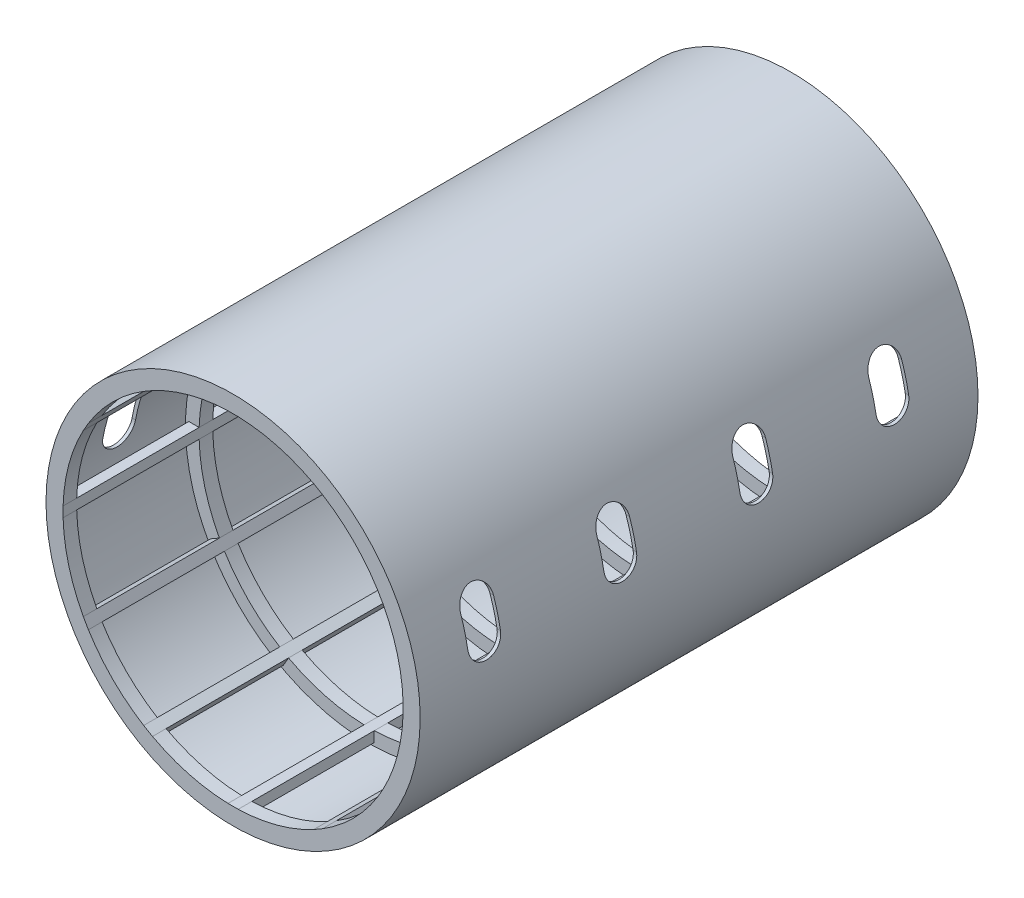
SolidWorks part; units mm, degrees
ref_plane "Front Plane" through (0, 0, 0) normal (0, 0, 1) x (1, 0, 0)
ref_plane "Top Plane" through (0, 0, 0) normal (0, 1, 0) x (1, 0, 0)
ref_plane "Right Plane" through (0, 0, 0) normal (1, 0, 0) x (0, 0, -1)
sketch "Sketch2" plane through (0, 0, 0) normal (0, 0, 1) x (1, 0, 0)
  circle A0 centre (0, 0) radius 25
  circle A1 centre (0, 0) radius 27
  dimension "D1" = 50
  dimension "D2" = 54
extrude "Boss-Extrude1" add sketch "Sketch2" along normal blind 2
sketch "Sketch3" plane through (0, 0, 2) normal (0, 0, 1) x (1, 0, 0)
  line L0 (12.6005, 23.3247) -> (11.1005, 20.7266)
  line L1 (-0.75, 26.5) -> (0.75, 26.5)
  line L2 (-0.75, 26.5) -> (-0.75, 23.5)
  line L3 (-0.75, 23.5) -> (0.75, 23.5)
  line L4 (0.75, 26.5) -> (0.75, 23.5)
  line L5 (-0.75, 26.5) -> (0.75, 23.5) construction
  line L6 (-0.75, 23.5) -> (0.75, 26.5) construction
  line L7 (12.6005, 23.3247) -> (13.8995, 22.5747)
  line L8 (13.8995, 22.5747) -> (12.3995, 19.9766)
  line L9 (11.1005, 20.7266) -> (12.3995, 19.9766)
  line L10 (22.5747, 13.8995) -> (19.9766, 12.3995)
  line L11 (22.5747, 13.8995) -> (23.3247, 12.6005)
  line L12 (23.3247, 12.6005) -> (20.7266, 11.1005)
  line L13 (19.9766, 12.3995) -> (20.7266, 11.1005)
  line L14 (26.5, 0.75) -> (23.5, 0.75)
  line L15 (26.5, 0.75) -> (26.5, -0.75)
  line L16 (26.5, -0.75) -> (23.5, -0.75)
  line L17 (23.5, 0.75) -> (23.5, -0.75)
  line L18 (23.3247, -12.6005) -> (20.7266, -11.1005)
  line L19 (23.3247, -12.6005) -> (22.5747, -13.8995)
  line L20 (22.5747, -13.8995) -> (19.9766, -12.3995)
  line L21 (20.7266, -11.1005) -> (19.9766, -12.3995)
  line L22 (13.8995, -22.5747) -> (12.3995, -19.9766)
  line L23 (13.8995, -22.5747) -> (12.6005, -23.3247)
  line L24 (12.6005, -23.3247) -> (11.1005, -20.7266)
  line L25 (12.3995, -19.9766) -> (11.1005, -20.7266)
  line L26 (0.75, -26.5) -> (0.75, -23.5)
  line L27 (0.75, -26.5) -> (-0.75, -26.5)
  line L28 (-0.75, -26.5) -> (-0.75, -23.5)
  line L29 (0.75, -23.5) -> (-0.75, -23.5)
  line L30 (-12.6005, -23.3247) -> (-11.1005, -20.7266)
  line L31 (-12.6005, -23.3247) -> (-13.8995, -22.5747)
  line L32 (-13.8995, -22.5747) -> (-12.3995, -19.9766)
  line L33 (-11.1005, -20.7266) -> (-12.3995, -19.9766)
  line L34 (-22.5747, -13.8995) -> (-19.9766, -12.3995)
  line L35 (-22.5747, -13.8995) -> (-23.3247, -12.6005)
  line L36 (-23.3247, -12.6005) -> (-20.7266, -11.1005)
  line L37 (-19.9766, -12.3995) -> (-20.7266, -11.1005)
  line L38 (-26.5, -0.75) -> (-23.5, -0.75)
  line L39 (-26.5, -0.75) -> (-26.5, 0.75)
  line L40 (-26.5, 0.75) -> (-23.5, 0.75)
  line L41 (-23.5, -0.75) -> (-23.5, 0.75)
  line L42 (-23.3247, 12.6005) -> (-20.7266, 11.1005)
  line L43 (-23.3247, 12.6005) -> (-22.5747, 13.8995)
  line L44 (-22.5747, 13.8995) -> (-19.9766, 12.3995)
  line L45 (-20.7266, 11.1005) -> (-19.9766, 12.3995)
  line L46 (-13.8995, 22.5747) -> (-12.3995, 19.9766)
  line L47 (-13.8995, 22.5747) -> (-12.6005, 23.3247)
  line L48 (-12.6005, 23.3247) -> (-11.1005, 20.7266)
  line L49 (-12.3995, 19.9766) -> (-11.1005, 20.7266)
  circle A0 centre (0, 0) radius 25 construction
  point P0 (0, 25)
  point P53 (0, 0)
  dimension "D1" = 1.5
  dimension "D2" = 3
  dimension "D3" = 12
extrude "Cut-Extrude1" cut sketch "Sketch3" against normal blind 25
pattern_linear "LPattern4" count 5 spacing 20 along (0, 0, 1) of bodies 102
sketch "Sketch4" plane through (0, 0, 0) normal (0, 0, -1) x (-1, 0, 0)
  circle A0 centre (0, 0) radius 27
  circle A1 centre (0, 0) radius 27.5
  dimension "D1" = 55
extrude "Boss-Extrude2" add sketch "Sketch4" against normal blind 82
sketch "Sketch5" plane through (0, 0, 0) normal (1, 0, 0) x (0, 0, -1)
  line L0 (-82, 7.2167) -> (0, 7.2167) construction
  line L1 (-82, 27.5) -> (-82, -27.5) construction
  line L2 (0, -27.5) -> (0, 27.5) construction
  line L3 (-72.1761, 8.8111) -> (-72.1761, 4.8111) construction
  line L4 (-69.7705, 8.8111) -> (-69.7705, 4.8111)
  line L5 (-74.5816, 8.8111) -> (-74.5816, 4.8111)
  line L6 (-54.5816, 8.8111) -> (-54.5816, 4.8111)
  line L7 (-49.7705, 8.8111) -> (-49.7705, 4.8111)
  line L8 (-52.1761, 8.8111) -> (-52.1761, 4.8111) construction
  line L9 (-34.5816, 8.8111) -> (-34.5816, 4.8111)
  line L10 (-29.7705, 8.8111) -> (-29.7705, 4.8111)
  line L11 (-32.1761, 8.8111) -> (-32.1761, 4.8111) construction
  line L12 (-14.5816, 8.8111) -> (-14.5816, 4.8111)
  line L13 (-9.7705, 8.8111) -> (-9.7705, 4.8111)
  line L14 (-12.1761, 8.8111) -> (-12.1761, 4.8111) construction
  arc A0 (-69.7705, 8.8111) -> (-74.5816, 8.8111) centre (-72.1761, 8.8111) ccw
  arc A1 (-74.5816, 4.8111) -> (-69.7705, 4.8111) centre (-72.1761, 4.8111) ccw
  arc A2 (-49.7705, 8.8111) -> (-54.5816, 8.8111) centre (-52.1761, 8.8111) ccw
  arc A3 (-54.5816, 4.8111) -> (-49.7705, 4.8111) centre (-52.1761, 4.8111) ccw
  arc A4 (-29.7705, 8.8111) -> (-34.5816, 8.8111) centre (-32.1761, 8.8111) ccw
  arc A5 (-34.5816, 4.8111) -> (-29.7705, 4.8111) centre (-32.1761, 4.8111) ccw
  arc A6 (-9.7705, 8.8111) -> (-14.5816, 8.8111) centre (-12.1761, 8.8111) ccw
  arc A7 (-14.5816, 4.8111) -> (-9.7705, 4.8111) centre (-12.1761, 4.8111) ccw
  point P8 (-72.1761, 6.8111)
  point P13 (0, 0)
  point P17 (-52.1761, 6.8111)
  point P24 (-32.1761, 6.8111)
  point P31 (-12.1761, 6.8111)
  dimension "D1" = 4
  dimension "D2" = 4
sketch "Sketch6" plane through (0, 0, 82) normal (0, 0, 1) x (1, 0, 0)
  line L0 (-13.8995, 22.5747) -> (-12.6005, 23.3247)
  line L1 (-12.6005, 23.3247) -> (-11.8449, 22.0159)
  line L2 (-11.8449, 22.0159) -> (-13.1439, 21.2659)
  line L3 (-13.1439, 21.2659) -> (-13.8995, 22.5747)
extrude "Boss-Extrude3" add sketch "Sketch6" against normal through all
sketch "Sketch7" plane through (0, 0, 82) normal (0, 0, 1) x (1, 0, 0)
  line L0 (-0.75, 26.5) -> (0.75, 26.5)
  line L1 (0.75, 26.5) -> (0.75, 24.9887)
  line L2 (0.75, 24.9887) -> (-0.75, 24.9887)
  line L3 (-0.75, 24.9887) -> (-0.75, 26.5)
  line L4 (11.8449, 22.0159) -> (12.6005, 23.3247)
  line L5 (12.6005, 23.3247) -> (13.8995, 22.5747)
  line L6 (13.8995, 22.5747) -> (13.1439, 21.2659)
  line L7 (13.1439, 21.2659) -> (11.8449, 22.0159)
  line L8 (21.2659, 13.1439) -> (22.5747, 13.8995)
  line L9 (22.5747, 13.8995) -> (23.3247, 12.6005)
  line L10 (23.3247, 12.6005) -> (22.0159, 11.8449)
  line L11 (22.0159, 11.8449) -> (21.2659, 13.1439)
  line L12 (24.9887, -0.75) -> (24.9887, 0.75)
  line L13 (24.9887, 0.75) -> (26.5, 0.75)
  line L14 (26.5, 0.75) -> (26.5, -0.75)
  line L15 (26.5, -0.75) -> (24.9887, -0.75)
  line L16 (21.2659, -13.1439) -> (22.0159, -11.8449)
  line L17 (22.0159, -11.8449) -> (23.3247, -12.6005)
  line L18 (23.3247, -12.6005) -> (22.5747, -13.8995)
  line L19 (22.5747, -13.8995) -> (21.2659, -13.1439)
  line L20 (11.8449, -22.0159) -> (13.1439, -21.2659)
  line L21 (13.1439, -21.2659) -> (13.8995, -22.5747)
  line L22 (13.8995, -22.5747) -> (12.6005, -23.3247)
  line L23 (12.6005, -23.3247) -> (11.8449, -22.0159)
  line L24 (-0.75, -24.9887) -> (0.75, -24.9887)
  line L25 (0.75, -24.9887) -> (0.75, -26.5)
  line L26 (0.75, -26.5) -> (-0.75, -26.5)
  line L27 (-0.75, -26.5) -> (-0.75, -24.9887)
  line L28 (-13.1439, -21.2659) -> (-11.8449, -22.0159)
  line L29 (-11.8449, -22.0159) -> (-12.6005, -23.3247)
  line L30 (-12.6005, -23.3247) -> (-13.8995, -22.5747)
  line L31 (-13.8995, -22.5747) -> (-13.1439, -21.2659)
  line L32 (-23.3247, -12.6005) -> (-22.0159, -11.8449)
  line L33 (-22.0159, -11.8449) -> (-21.2659, -13.1439)
  line L34 (-21.2659, -13.1439) -> (-22.5747, -13.8995)
  line L35 (-22.5747, -13.8995) -> (-23.3247, -12.6005)
  line L36 (-26.5, -0.75) -> (-26.5, 0.75)
  line L37 (-26.5, 0.75) -> (-24.9887, 0.75)
  line L38 (-24.9887, 0.75) -> (-24.9887, -0.75)
  line L39 (-24.9887, -0.75) -> (-26.5, -0.75)
  line L40 (-23.3247, 12.6005) -> (-22.5747, 13.8995)
  line L41 (-22.5747, 13.8995) -> (-21.2659, 13.1439)
  line L42 (-21.2659, 13.1439) -> (-22.0159, 11.8449)
  line L43 (-22.0159, 11.8449) -> (-23.3247, 12.6005)
extrude "Boss-Extrude4" add sketch "Sketch7" against normal through all
extrude "Cut-Extrude4" cut sketch "Sketch5" against normal mid plane 70
